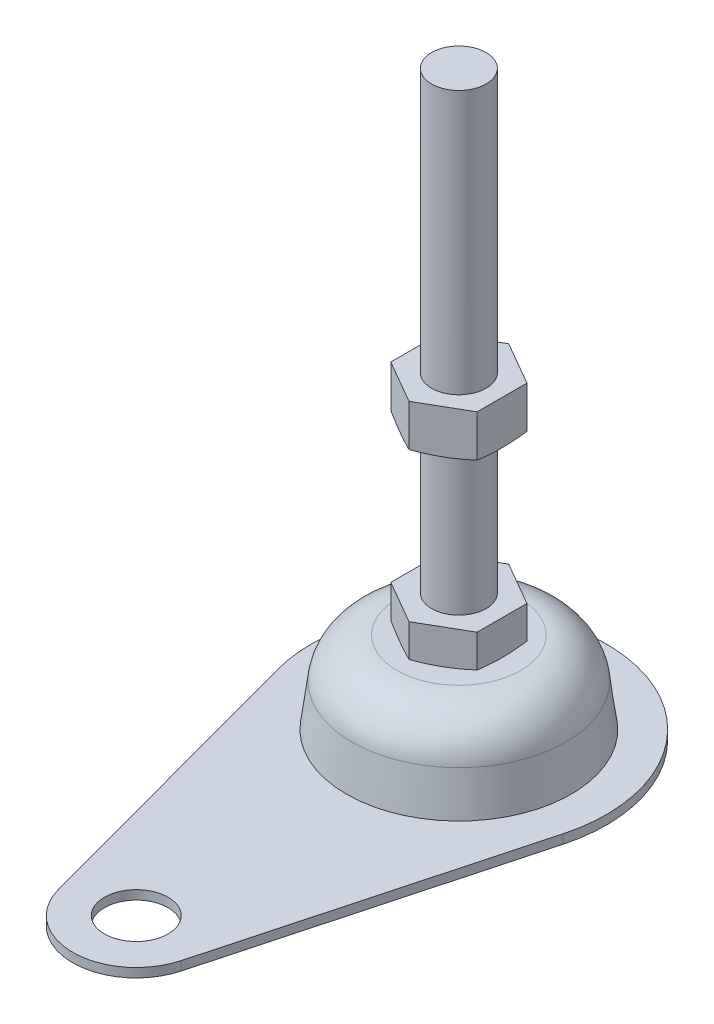
SolidWorks part; units mm, degrees
ref_plane "Front Plane" through (0, 0, 0) normal (0, 0, 1) x (1, 0, 0)
ref_plane "Top Plane" through (0, 0, 0) normal (0, 1, 0) x (1, 0, 0)
ref_plane "Right Plane" through (0, 0, 0) normal (1, 0, 0) x (0, 0, -1)
sketch "Sketch1" plane through (0, 0, 0) normal (0, 0, 1) x (1, 0, 0)
  line L0 (0, 0) -> (0, 128)
  line L1 (0, 128) -> (6, 128)
  line L2 (6, 128) -> (6, 20)
  line L3 (6, 20) -> (13.5972, 20)
  line L4 (0, 0) -> (25, 0)
  line L5 (25, 0) -> (23.5116, 11.3053)
  line L6 (0, 0) -> (0, 128) construction
  arc A0 (13.5972, 20) -> (23.5116, 11.3053) centre (13.5972, 10) cw
  dimension "FIX_2" = 10
  dimension "FIX_5" = 50
  dimension "FIX_1" = 128
  dimension "FIX_6" = 12
  dimension "FIX_3" = 82.5
  dimension "FIX_4" = 10
revolve "Revolve1" add sketch "Sketch1" angle 360 about L6
cosmetic thread "Thread1" parameters "NFIX_1"=10.106
sketch "Sketch2" plane through (0, 0, 0) normal (0, 1, 0) x (1, 0, 0)
  line L0 (-13.5164, -74.6479) -> (-31.3773, -8.4683)
  line L1 (31.3773, -8.4683) -> (13.5164, -74.6479)
  line L2 (0, -71) -> (0, 0) construction
  arc A0 (-31.3773, -8.4683) -> (31.3773, -8.4683) centre (0, 0) cw
  arc A1 (-13.5164, -74.6479) -> (13.5164, -74.6479) centre (0, -71) ccw
  circle A2 centre (0, -71) radius 7
  dimension "FIX_8" = 32.5
  dimension "FIX_9" = 14
  dimension "FIX_11" = 14
  dimension "FIX_10" = 71
extrude "Boss-Extrude1" add sketch "Sketch2" along normal blind 2
ref_plane "Plane1" through (0, 70, 0) normal (0, 1, 0) x (1, 0, 0)
sketch "Sketch3" plane through (0, 20, 0) normal (0, 1, 0) x (1, 0, 0)
  line L1 (0, -10.9697) -> (9.5, -5.4848)
  line L2 (9.5, -5.4848) -> (9.5, 5.4848)
  line L3 (9.5, 5.4848) -> (0, 10.9697)
  line L4 (0, 10.9697) -> (-9.5, 5.4848)
  line L5 (-9.5, 5.4848) -> (-9.5, -5.4848)
  line L6 (-9.5, -5.4848) -> (0, -10.9697)
  circle A0 centre (0, 0) radius 9.5 construction
  dimension "FIX_14" = 19
extrude "Boss-Extrude2" add sketch "Sketch3" along normal blind 8
sketch "Sketch5" plane through (0, 70, 0) normal (0, 1, 0) x (1, 0, 0)
  line L0 (0, -64.625) -> (0, 64.625) construction
  line L1 (0, 10.9697) -> (-9.5, 5.4848)
  line L2 (-9.5, 5.4848) -> (-9.5, -5.4848)
  line L3 (-9.5, -5.4848) -> (0, -10.9697)
  line L4 (0, -10.9697) -> (9.5, -5.4848)
  line L5 (9.5, -5.4848) -> (9.5, 5.4848)
  line L6 (9.5, 5.4848) -> (0, 10.9697)
  circle A0 centre (0, 0) radius 9.5 construction
  dimension "FIX_16" = 19
extrude "Boss-Extrude3" add sketch "Sketch5" against normal blind 10
sketch "Sketch4" plane through (0, 0, 0) normal (1, 0, 0) x (0, 0, -1)
  line L0 (8, 20) -> (10.9697, 20)
  line L1 (10.9697, 20) -> (10.9697, 20.7957)
  line L2 (10.9697, 20.7957) -> (8, 20)
  line L3 (0, 60) -> (0, 0) construction
  line L5 (8, 20) -> (8, 60) construction
  line L6 (8, 60) -> (10.9697, 60)
  line L7 (10.9697, 60) -> (10.9697, 60.7957)
  line L8 (10.9697, 60.7957) -> (8, 60)
  line L9 (35.75, 70) -> (-35.75, 70) construction
  dimension "FIX_18" = 15
  dimension "FIX_19" = 16
  dimension "FIX_20" = 10
revolve "Cut-Revolve1" cut sketch "Sketch4" angle 360 about L3
